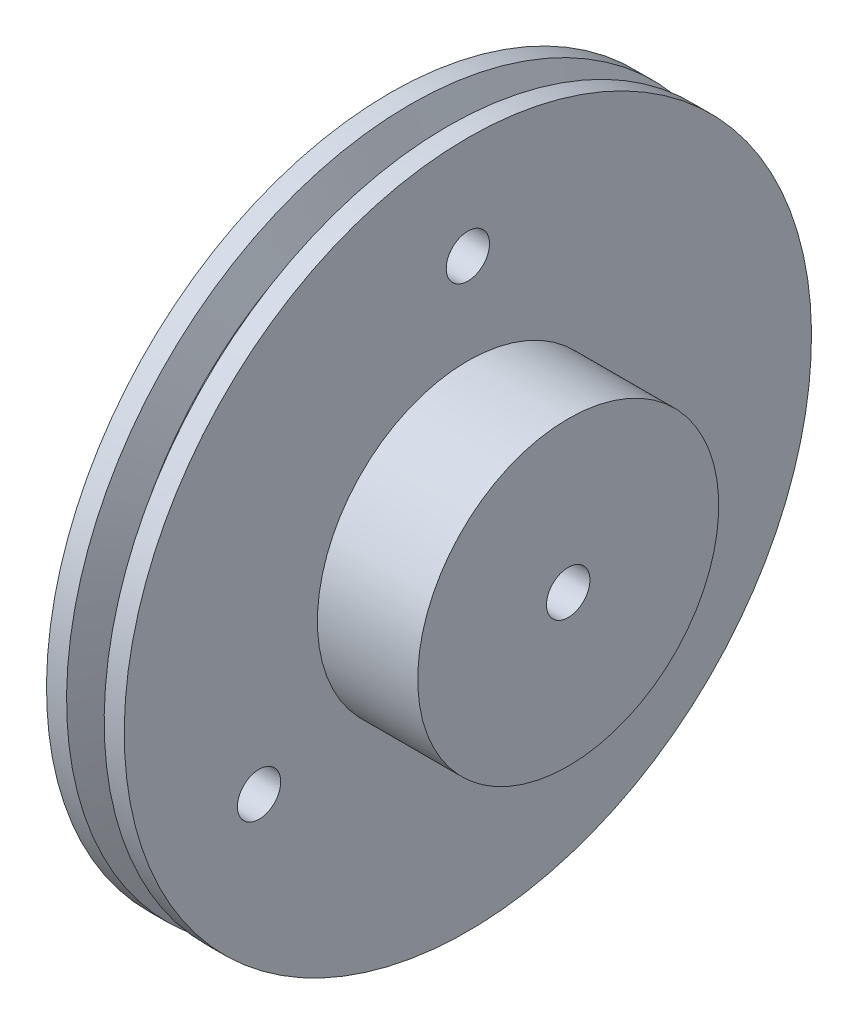
SolidWorks part; units mm, degrees
ref_plane "Front Plane" through (0, 0, 0) normal (0, 0, 1) x (1, 0, 0)
ref_plane "Top Plane" through (0, 0, 0) normal (0, 1, 0) x (1, 0, 0)
ref_plane "Right Plane" through (0, 0, 0) normal (1, 0, 0) x (0, 0, -1)
sketch "Sketch2" plane through (0, 0, 0) normal (0, 0, 1) x (1, 0, 0)
  line L0 (0, 0) -> (0, 86.995)
  line L6 (19.685, 86.995) -> (19.685, 38.1)
  line L7 (19.685, 38.1) -> (45.085, 38.1)
  line L8 (45.085, 38.1) -> (45.085, 0)
  line L9 (45.085, 0) -> (0, 0)
  line L10 (0, 86.995) -> (5.08, 86.995)
  line L12 (10.9037, 79.0575) -> (8.7813, 79.0575)
  line L14 (14.605, 86.995) -> (19.685, 86.995)
  line L15 (5.08, 86.995) -> (8.7813, 79.0575)
  line L16 (10.9037, 79.0575) -> (14.605, 86.995)
  point P4 (9.8425, 79.0575)
  dimension "D1" = 86.995
  dimension "D2" = 25
  dimension "D3" = 25
  dimension "D4" = 19.685
  dimension "D5" = 7.9375
  dimension "D6" = 9.525
  dimension "D7" = 5.08
  dimension "D8" = 25.4
  dimension "D9" = 38.1
revolve "Revolve1" add sketch "Sketch2" angle 360 about L9
sketch "Sketch3" plane through (45.085, 0, 0) normal (1, 0, 0) x (0, 0, -1)
  circle A0 centre (0, 0) radius 5.5
  dimension "D1" = 11
extrude "Cut-Extrude1" cut sketch "Sketch3" against normal through all
sketch "Sketch4" plane through (19.685, 0, 0) normal (1, 0, 0) x (0, 0, -1)
  circle A0 centre (0, 0) radius 61.0399 construction
  circle A1 centre (0, 61.0399) radius 5.4812
  circle A2 centre (52.8621, -30.5199) radius 5.4812
  circle A3 centre (-52.8621, -30.5199) radius 5.4812
  point P11 (0, 0)
  dimension "D1" = 3
extrude "Cut-Extrude2" cut sketch "Sketch4" against normal through all
